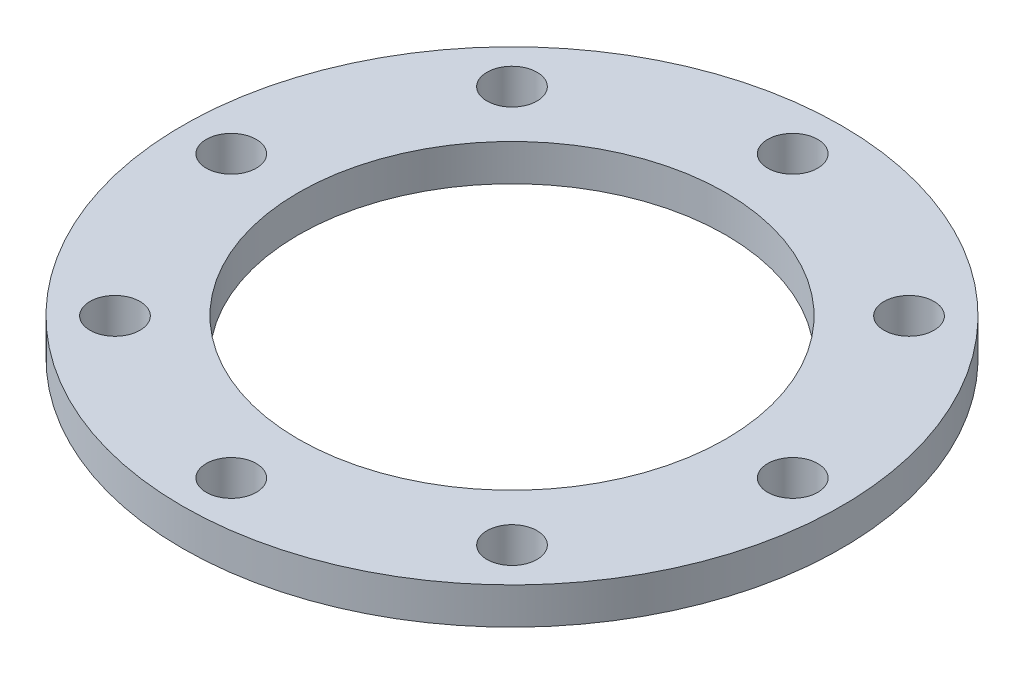
SolidWorks part; units mm, degrees
ref_plane "Front Plane" through (0, 0, 0) normal (0, 0, 1) x (1, 0, 0)
ref_plane "Top Plane" through (0, 0, 0) normal (0, 1, 0) x (1, 0, 0)
ref_plane "Right Plane" through (0, 0, 0) normal (1, 0, 0) x (0, 0, -1)
sketch "Sketch1" plane through (0, 0, 0) normal (0, 1, 0) x (1, 0, 0)
  circle A0 centre (0, 0) radius 17.5
  circle A1 centre (0, 0) radius 27
  dimension "D1" = 54
  dimension "D2" = 35
extrude "Boss-Extrude1" add sketch "Sketch1" along normal blind 3
sketch "Sketch2" plane through (0, 3, 0) normal (0, 1, 0) x (1, 0, 0)
  circle A0 centre (23, 0) radius 2.05
  dimension "D1" = 4.1
  dimension "D2" = 23
extrude "Cut-Extrude1" cut sketch "Sketch2" against normal through all
pattern_circular "CirPattern1" count 8 over 360 about axis through (0, 0, 0) along (0, 1, 0) of "Cut-Extrude1"
